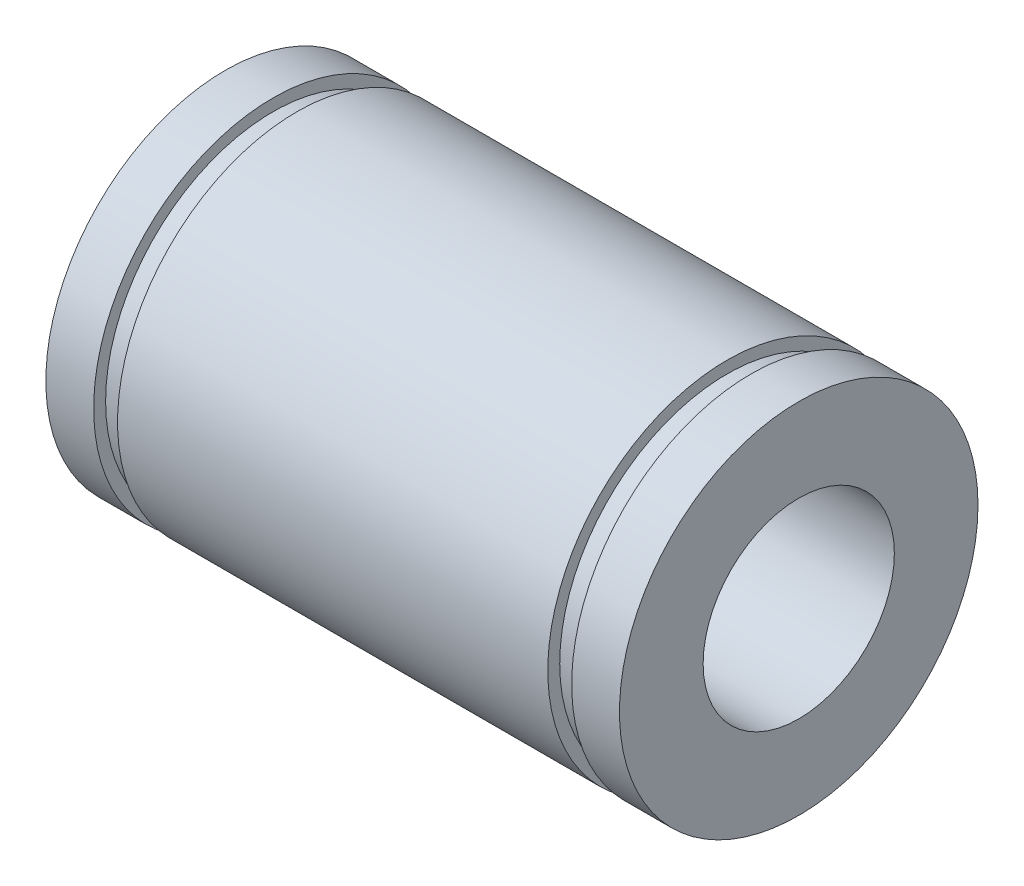
SolidWorks part; units mm, degrees
ref_plane "Front Plane" through (0, 0, 0) normal (0, 0, 1) x (1, 0, 0)
ref_plane "Top Plane" through (0, 0, 0) normal (0, 1, 0) x (1, 0, 0)
ref_plane "Right Plane" through (0, 0, 0) normal (1, 0, 0) x (0, 0, -1)
sketch "Sketch1" plane through (0, 0, 0) normal (1, 0, 0) x (0, 0, -1)
  circle A0 centre (0, 0) radius 4
  circle A1 centre (0, 0) radius 7.5
  dimension "D1" = 8
  dimension "D2" = 15
extrude "Boss-Extrude1" add sketch "Sketch1" along normal blind 2
sketch "Sketch2" plane through (2, 0, 0) normal (1, 0, 0) x (0, 0, -1)
  circle A0 centre (0, 0) radius 4
  circle A1 centre (0, 0) radius 7
  dimension "D1" = 14
extrude "Boss-Extrude2" add sketch "Sketch2" along normal blind 1
sketch "Sketch3" plane through (3, 0, 0) normal (1, 0, 0) x (0, 0, -1)
  circle A0 centre (0, 0) radius 4
  circle A1 centre (0, 0) radius 7.5
  dimension "D1" = 15
extrude "Boss-Extrude3" add sketch "Sketch3" along normal blind 18
sketch "Sketch4" plane through (21, 0, 0) normal (1, 0, 0) x (0, 0, -1)
  circle A0 centre (0, 0) radius 4
  circle A1 centre (0, 0) radius 7
  dimension "D1" = 14
extrude "Boss-Extrude4" add sketch "Sketch4" along normal blind 1
sketch "Sketch5" plane through (22, 0, 0) normal (1, 0, 0) x (0, 0, -1)
  circle A0 centre (0, 0) radius 4
  circle A1 centre (0, 0) radius 7.5
  dimension "D1" = 15
extrude "Boss-Extrude5" add sketch "Sketch5" along normal blind 2
